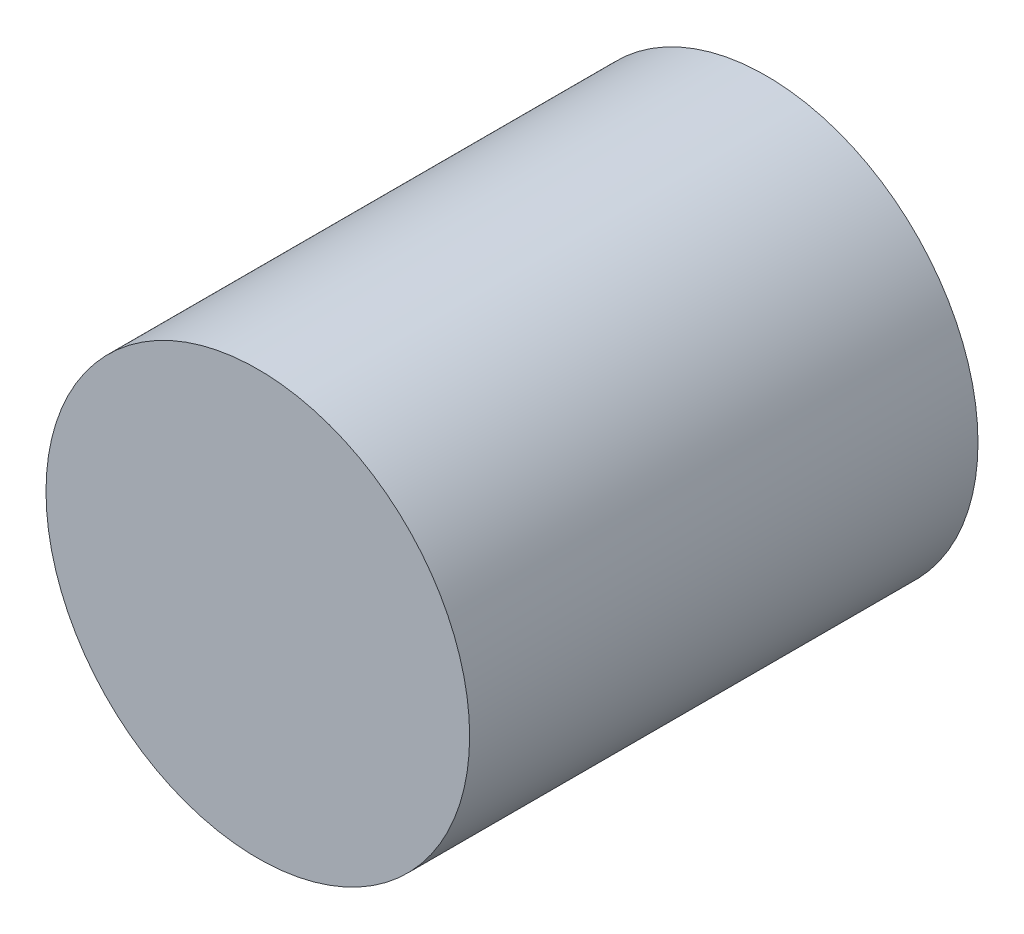
SolidWorks part; units mm, degrees
ref_plane "前视基准面" through (0, 0, 0) normal (0, 0, 1) x (1, 0, 0)
ref_plane "上视基准面" through (0, 0, 0) normal (0, 1, 0) x (1, 0, 0)
ref_plane "右视基准面" through (0, 0, 0) normal (1, 0, 0) x (0, 0, -1)
other "Configuration Table"
sketch "草图1" plane through (0, 0, 0) normal (0, 0, 1) x (1, 0, 0)
  line L0 (-20, -15) -> (20, -15)
  line L1 (20, -15) -> (20, 15)
  line L2 (20, 15) -> (-20, 15)
  line L3 (-20, 15) -> (-20, -15)
extrude "凸台-拉伸1" add sketch "草图1" along normal blind 12
sketch "草图2" plane through (0, 0, 12) normal (0, 0, 1) x (1, 0, 0)
  circle A0 centre (0, 0) radius 5
extrude "切除-拉伸1" cut sketch "草图2" against normal through all flip side to cut
